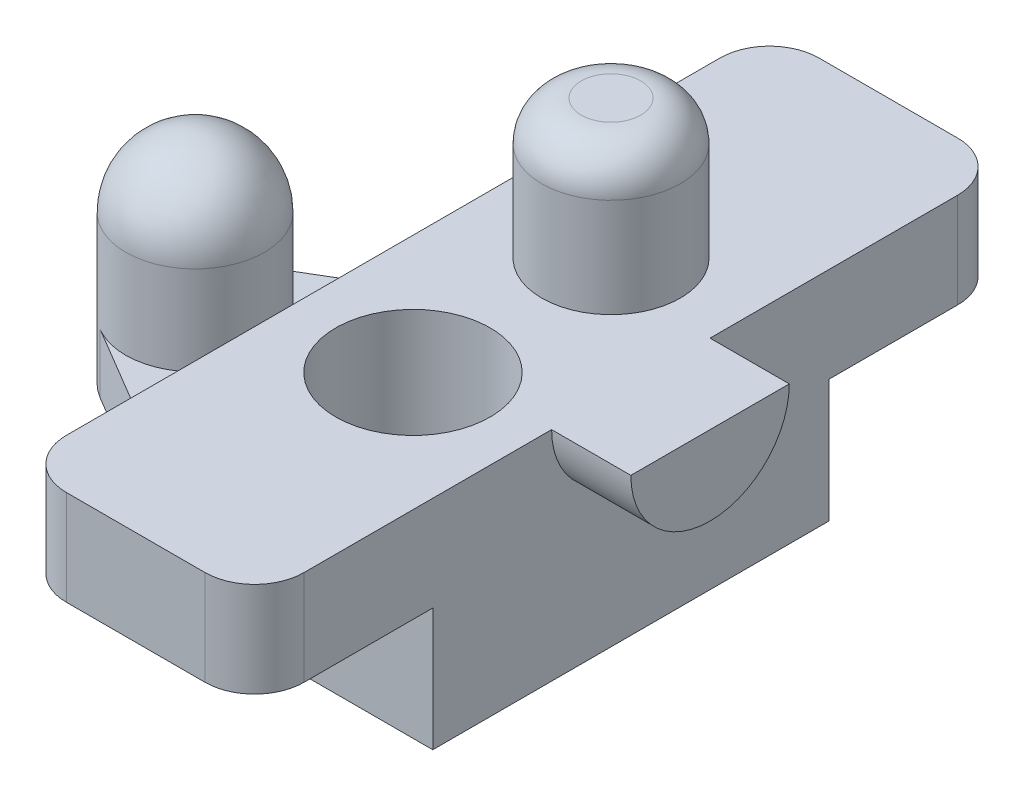
SolidWorks part; units mm, degrees
other "Markup1"
sketch "Sketch7" plane through (12, 7.5, 6.5) normal (0.0383, 0.9456, 0.3232) x (0.9932, -0.0006, -0.1161)
ref_plane "Front Plane" through (0, 0, 0) normal (0, 0, 1) x (1, 0, 0)
ref_plane "Top Plane" through (0, 0, 0) normal (0, 1, 0) x (1, 0, 0)
ref_plane "Right Plane" through (0, 0, 0) normal (1, 0, 0) x (0, 0, -1)
sketch "Sketch1" plane through (0, 0, 0) normal (0, 1, 0) x (1, 0, 0)
  line L0 (5, 5) -> (11, 5)
  line L1 (11, 5) -> (11, -5)
  line L2 (11, -5) -> (5, -5)
  line L3 (5, -5) -> (-0.8927, -1.5052)
  line L4 (5, 5) -> (-0.8927, 1.5052)
  arc A0 (-0.8927, 1.5052) -> (-0.8927, -1.5052) centre (0, 0) ccw
  point P11 (11, 0)
  dimension "D1" = 10
  dimension "D4" = 5
  dimension "D5" = 1.75
  dimension "D2" = 6
  dimension "D3" = 6
extrude "Boss-Extrude1" add sketch "Sketch1" against normal blind 1.5 contours L1 L2 L3 A0 L4 L0
sketch "Sketch2" plane through (0, 0, 0) normal (0, 1, 0) x (1, 0, 0)
  line L1 (5, 5) -> (11, 5)
  line L2 (5, 5) -> (5, -5)
  line L3 (5, -5) -> (11, -5)
  line L4 (11, 5) -> (11, -5)
  circle A0 centre (0, 0) radius 1.75
  dimension "D1" = 3.5
extrude "Boss-Extrude2" add sketch "Sketch2" along normal blind 4
sketch "Sketch3" plane through (0, 4, 0) normal (0, 1, 0) x (1, 0, 0)
  line L0 (5, 5) -> (11, 5)
  line L4 (-55, 0) -> (55, 0) construction
  line L6 (5, -5) -> (11, -5)
  line L7 (5, 5) -> (5, 8.25)
  line L8 (6.25, 9.5) -> (9.75, 9.5)
  line L9 (11, 8.25) -> (11, 5)
  line L10 (11, -8.25) -> (11, -5)
  line L11 (6.25, -9.5) -> (9.75, -9.5)
  line L12 (5, -5) -> (5, -8.25)
  arc A4 (5, 8.25) -> (6.25, 9.5) centre (6.25, 8.25) cw
  arc A5 (11, 8.25) -> (9.75, 9.5) centre (9.75, 8.25) ccw
  arc A6 (11, -8.25) -> (9.75, -9.5) centre (9.75, -8.25) cw
  arc A7 (5, -8.25) -> (6.25, -9.5) centre (6.25, -8.25) ccw
  dimension "D2" = 1.25
  dimension "D1" = 4.5
extrude "Boss-Extrude3" add sketch "Sketch3" against normal blind 2.4
fillet "Fillet1" radius 1.75 1 edges at (0, 4, 1.75)
sketch "Sketch4" plane through (0, 4, 0) normal (0, 1, 0) x (1, 0, 0)
  line L0 (5, 8.25) -> (5, -8.25) construction
  circle A0 centre (8, 2.5) radius 1.75
  dimension "D1" = 3.5
  dimension "D2" = 3
  dimension "D3" = 2.5
extrude "Boss-Extrude4" add sketch "Sketch4" along normal blind 3.5
fillet "Fillet2" radius 1 1 edges at (8, 7.5, -0.75)
sketch "Sketch5" plane through (0, 4, 0) normal (0, 1, 0) x (1, 0, 0)
  line L0 (5, 8.25) -> (5, -8.25) construction
  circle A0 centre (8, -2.5) radius 1.95
  dimension "D1" = 3.9
  dimension "D2" = 2.5
  dimension "D3" = 3
extrude "Cut-Extrude1" cut sketch "Sketch5" against normal blind 3.75
sketch "Sketch6" plane through (11, 0, 0) normal (1, 0, 0) x (0, 0, -1)
  line L0 (-8.25, 4) -> (8.25, 4) construction
  line L1 (-2, 4) -> (2, 4)
  arc A0 (-2, 4) -> (2, 4) centre (0, 4) ccw
  dimension "D1" = 4
extrude "Boss-Extrude5" add sketch "Sketch6" along normal blind 2
